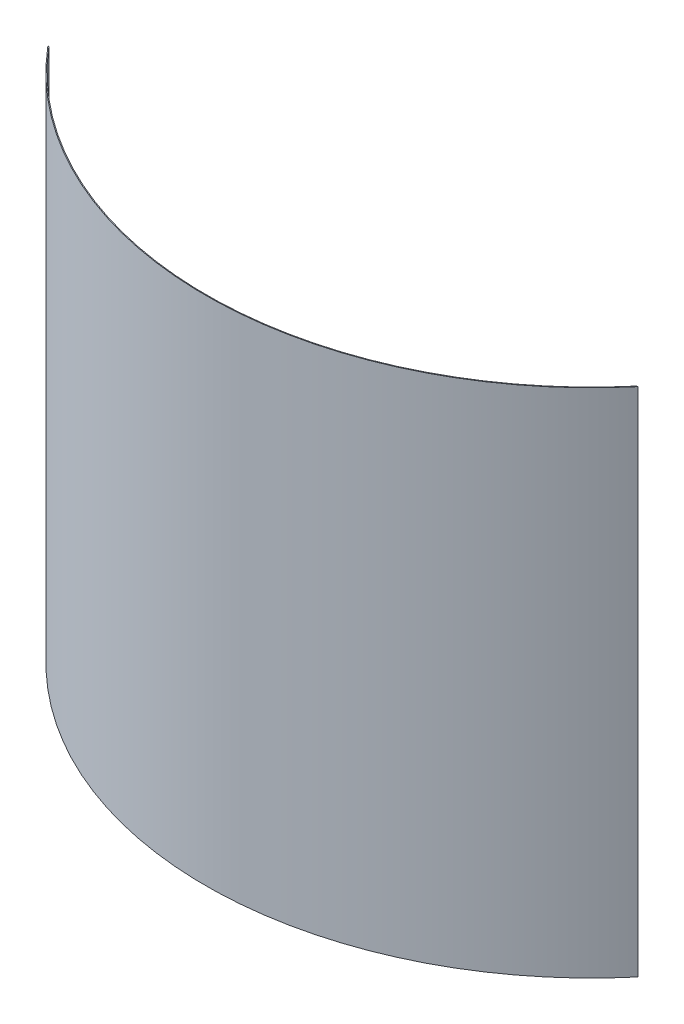
SolidWorks part; units mm, degrees
ref_plane "Front Plane" through (0, 0, 0) normal (0, 0, 1) x (1, 0, 0)
ref_plane "Top Plane" through (0, 0, 0) normal (0, 1, 0) x (1, 0, 0)
ref_plane "Right Plane" through (0, 0, 0) normal (1, 0, 0) x (0, 0, -1)
sketch "Sketch1" plane through (0, 0, 0) normal (0, 1, 0) x (1, 0, 0)
  line L0 (292.1, -247.3794) -> (293.1394, -247.3794)
  line L1 (-292.1, -247.3794) -> (-293.1394, -247.3794)
  arc A0 (292.1, -247.3794) -> (-292.1, -247.3794) centre (0, 0) cw
  arc A1 (-293.1394, -247.3794) -> (293.1394, -247.3794) centre (0, 0) ccw
  dimension "D1" = 382.778
  dimension "D3" = 0.7937
  dimension "D2" = 584.2
extrude "Boss-Extrude2" add sketch "Sketch1" along normal blind 508 contours A0 L1 A1 L0
